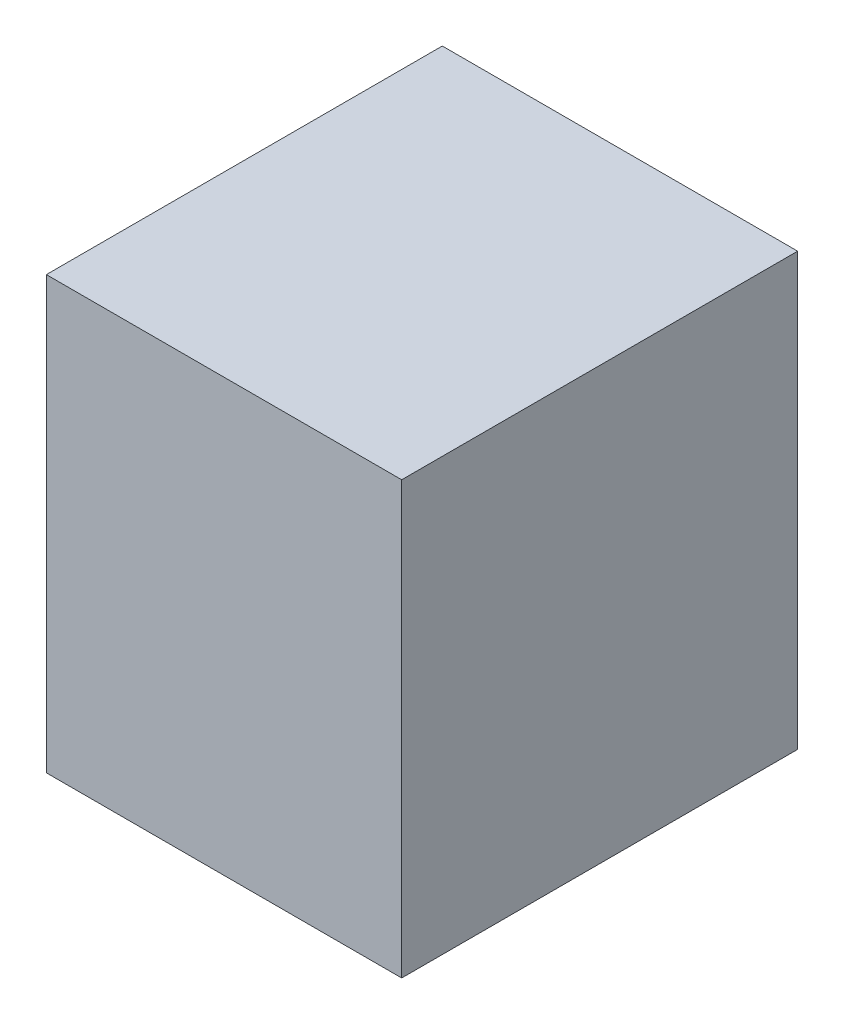
SolidWorks part; units mm, degrees
ref_plane "Front Plane" through (0, 0, 0) normal (0, 0, 1) x (1, 0, 0)
ref_plane "Top Plane" through (0, 0, 0) normal (0, 1, 0) x (1, 0, 0)
ref_plane "Right Plane" through (0, 0, 0) normal (1, 0, 0) x (0, 0, -1)
sketch "Sketch1" plane through (0, 0, 0) normal (1, 0, 0) x (0, 0, -1)
  line L1 (-3.9, -4.25) -> (3.9, -4.25)
  line L2 (-3.9, -4.25) -> (-3.9, 4.25)
  line L3 (-3.9, 4.25) -> (3.9, 4.25)
  line L4 (3.9, -4.25) -> (3.9, 4.25)
  line L5 (-3.9, -4.25) -> (3.9, 4.25) construction
  line L6 (-3.9, 4.25) -> (3.9, -4.25) construction
  point P0 (0, 0)
  dimension "D1" = 7.8
  dimension "D2" = 8.5
extrude "Boss-Extrude1" add sketch "Sketch1" along normal blind 7
